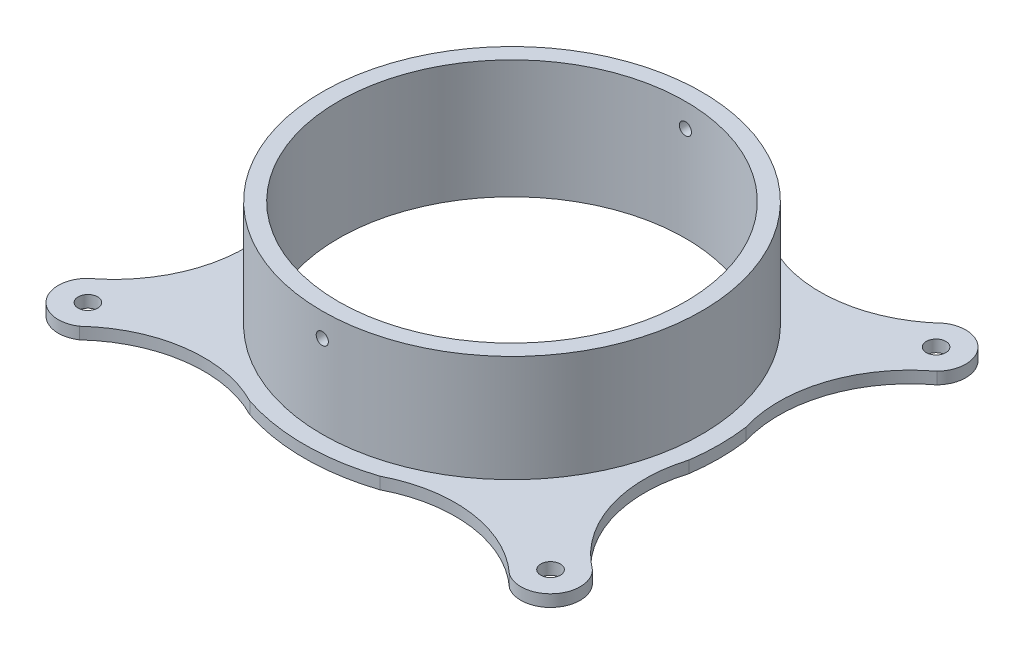
SolidWorks part; units mm, degrees
ref_plane "前视基准面" through (0, 0, 0) normal (0, 0, 1) x (1, 0, 0)
ref_plane "上视基准面" through (0, 0, 0) normal (0, 1, 0) x (1, 0, 0)
ref_plane "右视基准面" through (0, 0, 0) normal (1, 0, 0) x (0, 0, -1)
sketch "草图1" plane through (0, 0, 0) normal (0, 1, 0) x (1, 0, 0)
  line L0 (-64.683, 0) -> (63.4787, 0) construction
  line L1 (0, 51.7) -> (0, -47.2719) construction
  line L3 (39, -32.5) -> (-39, -32.5) construction
  line L4 (39, -32.5) -> (39, 32.5) construction
  line L5 (39, 32.5) -> (-39, 32.5) construction
  line L6 (-39, -32.5) -> (-39, 32.5) construction
  line L7 (39, -32.5) -> (-39, 32.5) construction
  line L8 (39, 32.5) -> (-39, -32.5) construction
  circle A0 centre (0, 0) radius 27.5 construction
  arc A2 (36.2479, 36.6744) -> (42.6097, 29.0402) centre (39, 32.5) cw
  arc A3 (-36.2479, -36.6744) -> (-42.6097, -29.0402) centre (-39, -32.5) cw
  arc A4 (36.2479, -36.6744) -> (42.6097, -29.0402) centre (39, -32.5) ccw
  arc A5 (-34.6689, 4.8029) -> (-34.6689, -4.8029) centre (0, 0) ccw
  arc A8 (-36.2479, 36.6744) -> (-42.6097, 29.0402) centre (-39, 32.5) ccw
  arc A15 (-10.9759, -33.2345) -> (10.9759, -33.2345) centre (0, 0) ccw
  arc A16 (34.6689, -4.8029) -> (34.6689, 4.8029) centre (0, 0) ccw
  arc A17 (10.9759, 33.2345) -> (-10.9759, 33.2345) centre (0, 0) ccw
  arc A18 (-10.9759, 33.2345) -> (-36.2479, 36.6744) centre (-21.1666, 52.9189) cw
  arc A19 (-34.6689, 4.8029) -> (-42.6097, 29.0402) centre (-55.8683, 11.2769) ccw
  arc A20 (-34.6689, -4.8029) -> (-42.6097, -29.0402) centre (-55.8683, -11.2769) cw
  arc A21 (-10.9759, -33.2345) -> (-36.2479, -36.6744) centre (-21.1666, -52.9189) ccw
  arc A22 (10.9759, -33.2345) -> (36.2479, -36.6744) centre (21.1666, -52.9189) cw
  arc A23 (34.6689, -4.8029) -> (42.6097, -29.0402) centre (55.8683, -11.2769) ccw
  arc A24 (34.6689, 4.8029) -> (42.6097, 29.0402) centre (55.8683, 11.2769) cw
  arc A25 (10.9759, 33.2345) -> (36.2479, 36.6744) centre (21.1666, 52.9189) ccw
  dimension "D1" = 65
  dimension "D2" = 55
  dimension "D3" = 78
  dimension "D4" = 70
extrude "凸台-拉伸2" add sketch "草图1" along normal blind 2
ref_plane "基准面1" through (0, 2, 0) normal (0, 1, 0) x (1, 0, 0)
sketch "草图2" plane through (0, 2, 0) normal (0, 1, 0) x (1, 0, 0)
  circle A0 centre (0, 0) radius 32
  dimension "D1" = 64
extrude "凸台-拉伸3" add sketch "草图2" along normal blind 18
ref_plane "基准面2" through (0, 20, 0) normal (0, 1, 0) x (1, 0, 0)
sketch "草图3" plane through (0, 20, 0) normal (0, 1, 0) x (1, 0, 0)
  circle A0 centre (0, 0) radius 25
  dimension "D1" = 50
ref_plane "基准面3" through (0, 0, 0) normal (1, 0, 0) x (0, 0, -1)
ref_plane "基准面4" through (0, 0, 0) normal (0, 0, 1) x (1, 0, 0)
hole_wizard "M2.5 螺纹孔1" positions "草图9" profile "草图10" tap size "M2.5" standard "GB"
sketch "草图9" plane through (0, 0, 0) normal (0, 0, 1) x (1, 0, 0)
  line L1 (25, 20) -> (-25, 20) construction
  point P0 (0, 16)
  dimension "D1" = 4
sketch "草图10" plane through (0, 16, 0) normal (1, 0, 0) x (0, 1, 0)
  line L0 (0, 0) -> (0, 37.5)
  line L1 (0, 37.5) -> (1.025, 37.5)
  line L2 (1.025, 37.5) -> (1.025, 0)
  line L5 (1.025, 0) -> (0, 0)
  line L11 (0, -6.35) -> (0, 107.95) construction
  dimension "通孔螺纹孔钻头直径" = 2.05
  dimension "通孔螺纹孔钻头深度" = 37.5
cosmetic thread "孔螺蚊线21" parameters "D2"=2.5
mirror "镜向3" about plane through (0, 0, 0) normal (0, 0, 1) of "M2.5 螺纹孔1"
ref_plane "基准面5" through (0, 0, 0) normal (0, -1, 0) x (-1, 0, 0)
sketch "草图21" plane through (0, 0, 0) normal (0, -1, 0) x (-1, 0, 0)
  line L1 (-39, 32.5) -> (39, 32.5) construction
  line L2 (-39, 32.5) -> (-39, -32.5) construction
  line L3 (-39, -32.5) -> (39, -32.5) construction
  line L4 (39, 32.5) -> (39, -32.5) construction
  circle A0 centre (-39, 32.5) radius 3
  circle A1 centre (39, 32.5) radius 3
  circle A2 centre (-39, -32.5) radius 3
  circle A3 centre (39, -32.5) radius 3
hole_wizard "M4 螺纹孔2" positions "草图24" profile "草图25" tap size "M4" standard "GB" end condition through all
sketch "草图24" plane through (0, 20, 0) normal (0, 1, 0) x (1, 0, 0)
  point P0 (-39, 32.5)
  point P3 (-39, -32.5)
  point P6 (39, -32.5)
  point P9 (39, 32.5)
sketch "草图25" plane through (-39, 20, -32.5) normal (1, 0, 0) x (0, 0, 1)
  line L0 (0, 0) -> (0, 20)
  line L1 (0, 20) -> (1.65, 20)
  line L2 (1.65, 20) -> (1.65, 0)
  line L5 (1.65, 0) -> (0, 0)
  line L11 (0, -6.35) -> (0, 107.95) construction
  dimension "通孔螺纹孔钻头直径" = 3.3
  dimension "通孔螺纹孔钻头深度" = 20
cosmetic thread "孔螺蚊线14" parameters "D2"=4
cosmetic thread "孔螺蚊线15" parameters "D2"=4
cosmetic thread "孔螺蚊线16" parameters "D2"=4
cosmetic thread "孔螺蚊线17" parameters "D2"=4
ref_plane "基准面6" through (0, 20, 0) normal (0, 1, 0) x (1, 0, 0)
hole_wizard "M60 螺纹孔2" positions "草图29" profile "草图30" tap size "M60" standard "GB" end condition through all
sketch "草图29" plane through (0, 20, 0) normal (0, 1, 0) x (1, 0, 0)
  point P0 (0, 0)
sketch "草图30" plane through (0, 20, 0) normal (1, 0, 0) x (0, 0, 1)
  line L0 (0, 0) -> (0, 20)
  line L1 (0, 20) -> (29.25, 20)
  line L2 (29.25, 20) -> (29.25, 0)
  line L5 (29.25, 0) -> (0, 0)
  line L11 (0, -6.35) -> (0, 107.95) construction
  dimension "通孔螺纹孔钻头直径" = 58.5
  dimension "通孔螺纹孔钻头深度" = 20
cosmetic thread "孔螺蚊线23" parameters "D2"=60
